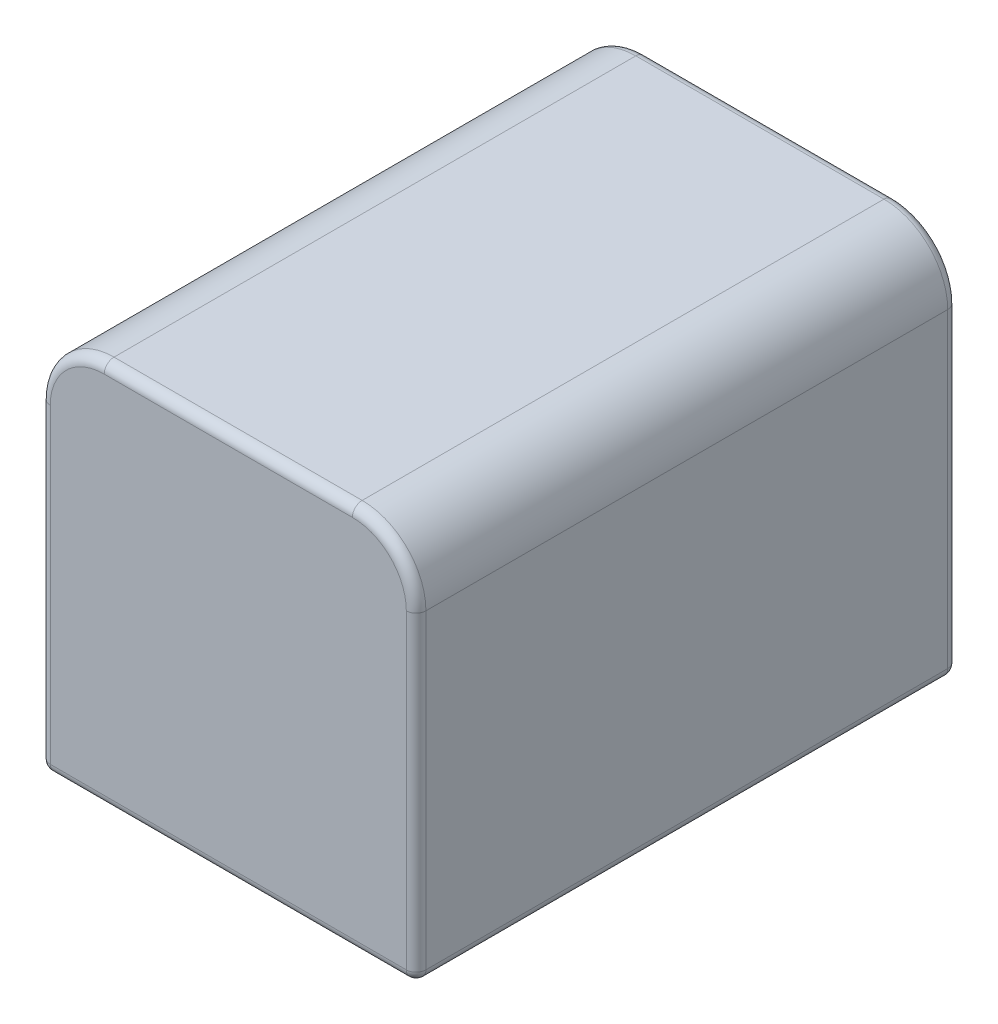
SolidWorks part; units mm, degrees
ref_plane "Front" through (0, 0, 0) normal (0, 0, 1) x (1, 0, 0)
ref_plane "Top" through (0, 0, 0) normal (0, 1, 0) x (1, 0, 0)
ref_plane "Right" through (0, 0, 0) normal (1, 0, 0) x (0, 0, -1)
sketch "Sketch1" plane through (0, 0, 0) normal (0, 0, 1) x (1, 0, 0)
  line L0 (0, 0) -> (0, 44.9113) construction
  line L2 (-19.15, 0) -> (19.15, 0)
  line L3 (-19.15, 0) -> (-19.15, 32.7)
  line L4 (-12.65, 39.2) -> (12.65, 39.2)
  line L5 (19.15, 0) -> (19.15, 32.7)
  arc A0 (-19.15, 32.7) -> (-12.65, 39.2) centre (-12.65, 32.7) cw
  arc A1 (19.15, 32.7) -> (12.65, 39.2) centre (12.65, 32.7) ccw
  dimension "D3" = 6.5
  dimension "D1" = 38.3
  dimension "D2" = 39.2
extrude "Extrude1" add sketch "Sketch1" along normal blind 55.2
fillet "Fillet1" radius 1 14 edges at (19.15, 16.35, 0) (17.2462, 37.2962, 0) (0, 39.2, 0) (-17.2462, 37.2962, 0) (19.15, 16.35, 55.2) (17.2462, 37.2962, 55.2) (0, 39.2, 55.2) (-17.2462, 37.2962, 55.2) (0, 0, 0) (0, 0, 55.2) (19.15, 0, 27.6) (-19.15, 0, 27.6) (-19.15, 16.35, 0) (-19.15, 16.35, 55.2)
